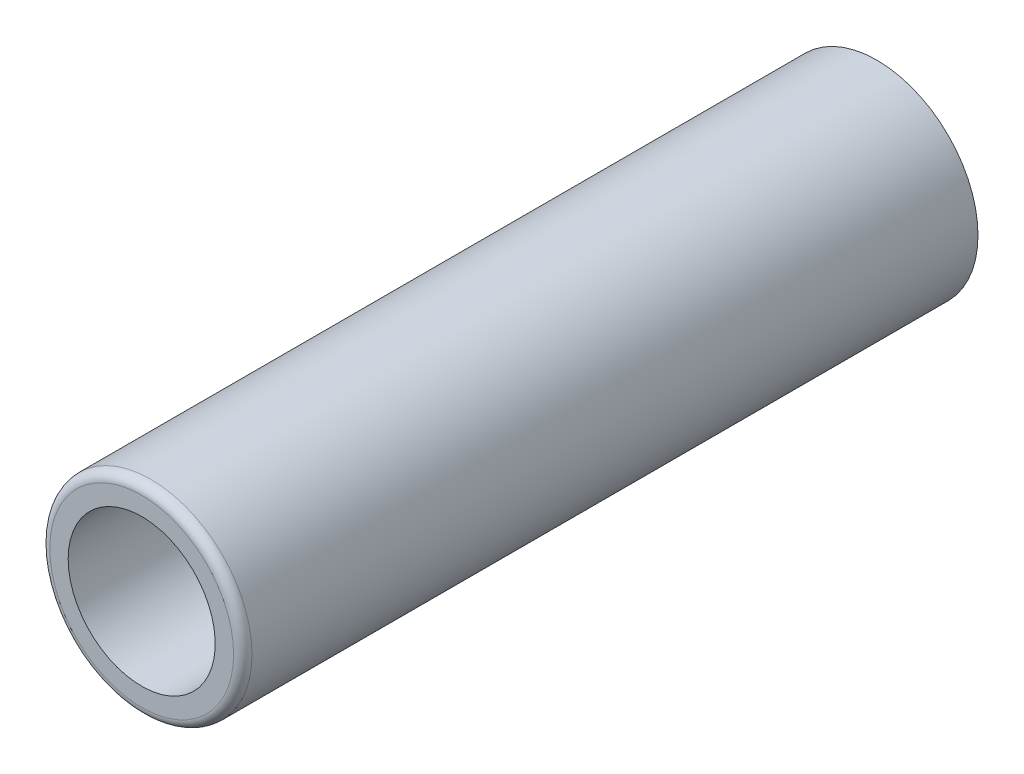
SolidWorks part; units mm, degrees
ref_plane "Piano frontale" through (0, 0, 0) normal (0, 0, 1) x (1, 0, 0)
ref_plane "Piano superiore" through (0, 0, 0) normal (0, 1, 0) x (1, 0, 0)
ref_plane "Piano destro" through (0, 0, 0) normal (1, 0, 0) x (0, 0, -1)
sketch "Schizzo1" plane through (0, 0, 0) normal (0, 0, 1) x (1, 0, 0)
  circle A0 centre (0, 0) radius 55
  dimension "D1" = 110
extrude "Estrusione-Estrusione1" add sketch "Schizzo1" along normal blind 400
sketch "Schizzo2" plane through (0, 0, 0) normal (0, 0, -1) x (-1, 0, 0)
  circle A0 centre (0, 0) radius 40
  dimension "D1" = 80
extrude "Taglio-Estrusione1" cut sketch "Schizzo2" against normal through all
fillet "Raccordo1" radius 5 1 edges at (55, 0, 400)
